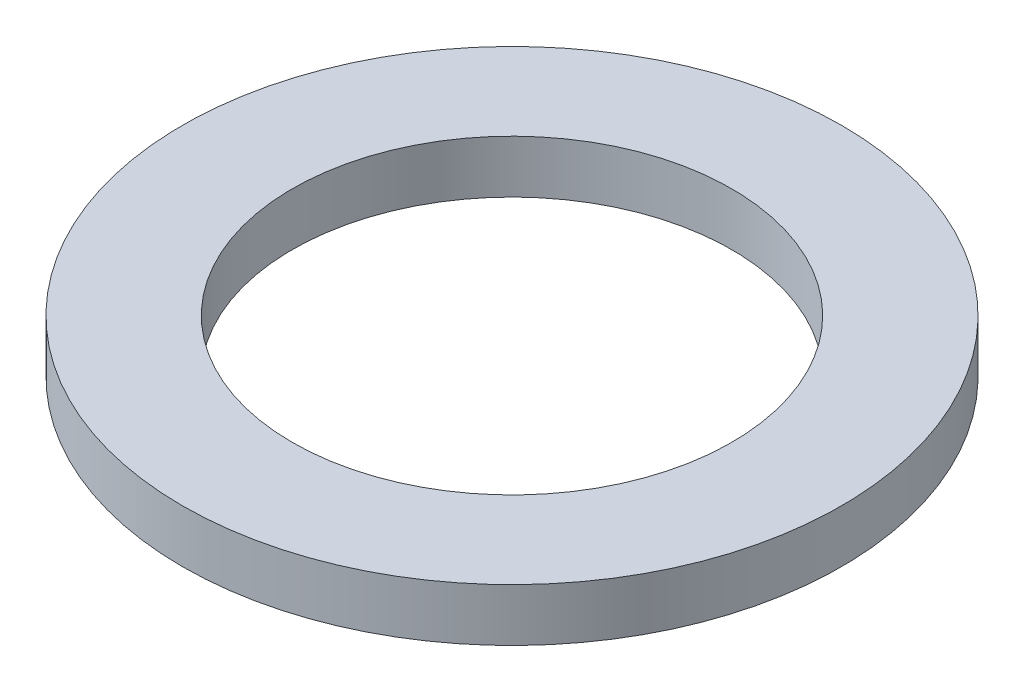
SolidWorks part; units mm, degrees
ref_plane "Front Plane" through (0, 0, 0) normal (0, 0, 1) x (1, 0, 0)
ref_plane "Top Plane" through (0, 0, 0) normal (0, 1, 0) x (1, 0, 0)
ref_plane "Right Plane" through (0, 0, 0) normal (1, 0, 0) x (0, 0, -1)
sketch "Sketch1" plane through (0, 0, 0) normal (0, 1, 0) x (1, 0, 0)
  circle A0 centre (0, 0) radius 9.525
  dimension "OD" = 19.05
extrude "Boss-Extrude1" add sketch "Sketch1" along normal blind 1.524
sketch "Sketch5" plane through (0, 1.524, 0) normal (0, 1, 0) x (-1, 0, 0)
  circle A0 centre (0, 0) radius 6.35
  dimension "ID" = 12.7
extrude "Cut-Extrude1" cut sketch "Sketch5" against normal through all
